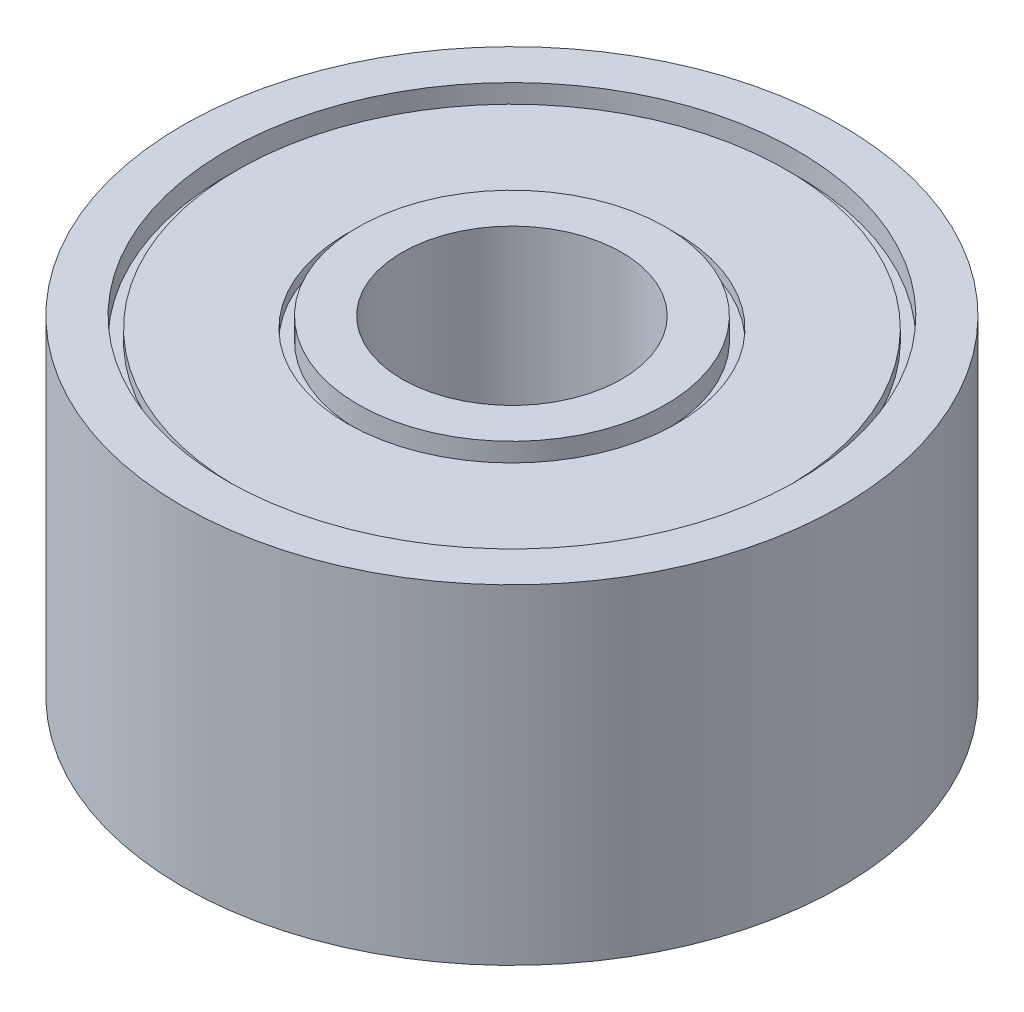
SolidWorks part; units mm, degrees
ref_plane "Front Plane" through (0, 0, 0) normal (0, 0, 1) x (1, 0, 0)
ref_plane "Top Plane" through (0, 0, 0) normal (0, 1, 0) x (1, 0, 0)
ref_plane "Right Plane" through (0, 0, 0) normal (1, 0, 0) x (0, 0, -1)
sketch "Sketch1" plane through (0, 0, 0) normal (1, 0, 0) x (0, 0, -1)
  line L0 (-3, 0) -> (-3, -1.5)
  line L1 (0, 0) -> (-64.4653, 0) construction
  line L2 (-3, -1.5) -> (-2.6, -1.5)
  line L3 (-2.6, -1.5) -> (-2.6, -1.3)
  line L4 (0, 0) -> (0, -106.3845) construction
  line L5 (-2.6, -1.3) -> (-2.5, -1.3)
  line L6 (-2.5, -1.3) -> (-2.5, -1.4)
  line L7 (-2.5, -1.4) -> (-1.5, -1.4)
  line L8 (-1.5, -1.4) -> (-1.5, -1.3)
  line L9 (-1.5, -1.3) -> (-1.4, -1.3)
  line L10 (-1.4, -1.3) -> (-1.4, -1.5)
  line L11 (-1.4, -1.5) -> (-1, -1.5)
  line L12 (-1, -1.5) -> (-1, 0)
  line L13 (-1, 0) -> (-3, 0)
  line L14 (-2, -1.4) -> (-2, -1.5) construction
  line L15 (-2.6, -1.5) -> (-1.4, -1.5) construction
  dimension "D1" = 3
  dimension "D2" = 1
  dimension "D3" = 0.4
  dimension "D4" = 0.4
  dimension "D5" = 1.5
  dimension "D6" = 0.1
revolve "Revolve1" add sketch "Sketch1" angle 360 about L4
mirror "Mirror1" about plane through (0, 0, 1) normal (0, 1, 0) of "Revolve1"
